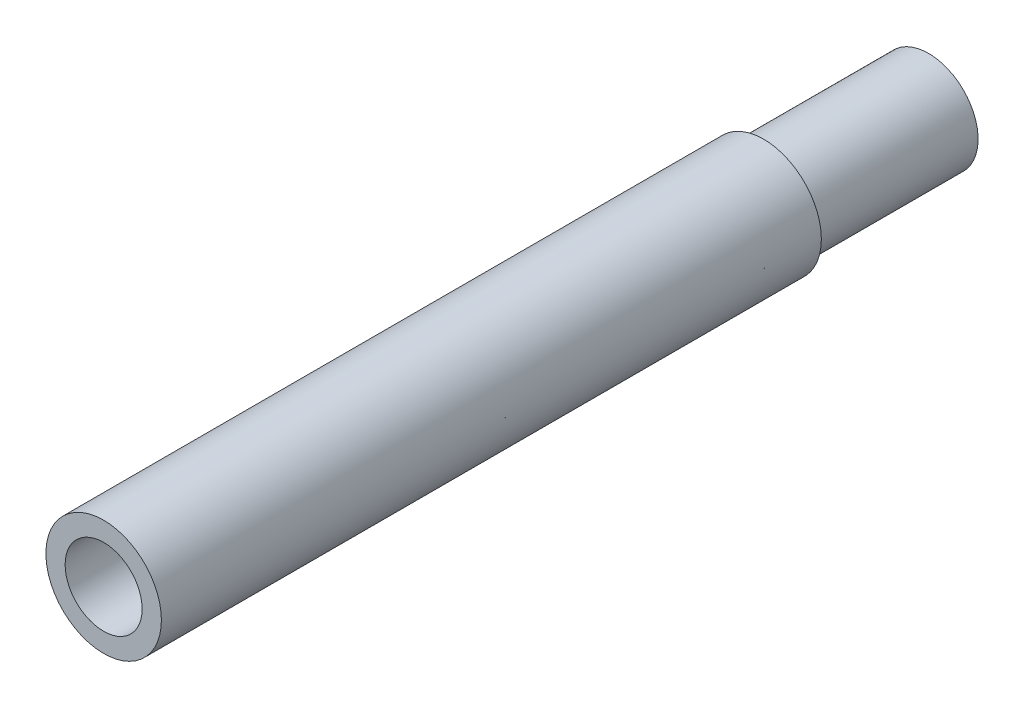
SolidWorks part; units mm, degrees
ref_plane "Front Plane" through (0, 0, 0) normal (0, 0, 1) x (1, 0, 0)
ref_plane "Top Plane" through (0, 0, 0) normal (0, 1, 0) x (1, 0, 0)
ref_plane "Right Plane" through (0, 0, 0) normal (1, 0, 0) x (0, 0, -1)
sketch "Sketch2" plane through (0, 0, 0) normal (0, 0, 1) x (1, 0, 0)
  circle A0 centre (0, 0) radius 7
  circle A1 centre (0, 0) radius 10.5
  dimension "D1" = 14
  dimension "D2" = 21
extrude "Boss-Extrude1" add sketch "Sketch2" along normal blind 120
sketch "Sketch4" plane through (0, 0, 0) normal (0, 0, -1) x (-1, 0, 0)
  circle A0 centre (0, 0) radius 7
  circle A1 centre (0, 0) radius 9
  dimension "D1" = 14
  dimension "D2" = 18
extrude "Boss-Extrude2" add sketch "Sketch4" along normal blind 30
fillet "Fillet2" [suppressed] radius 1
fillet "Fillet3" [suppressed] radius 1.75
